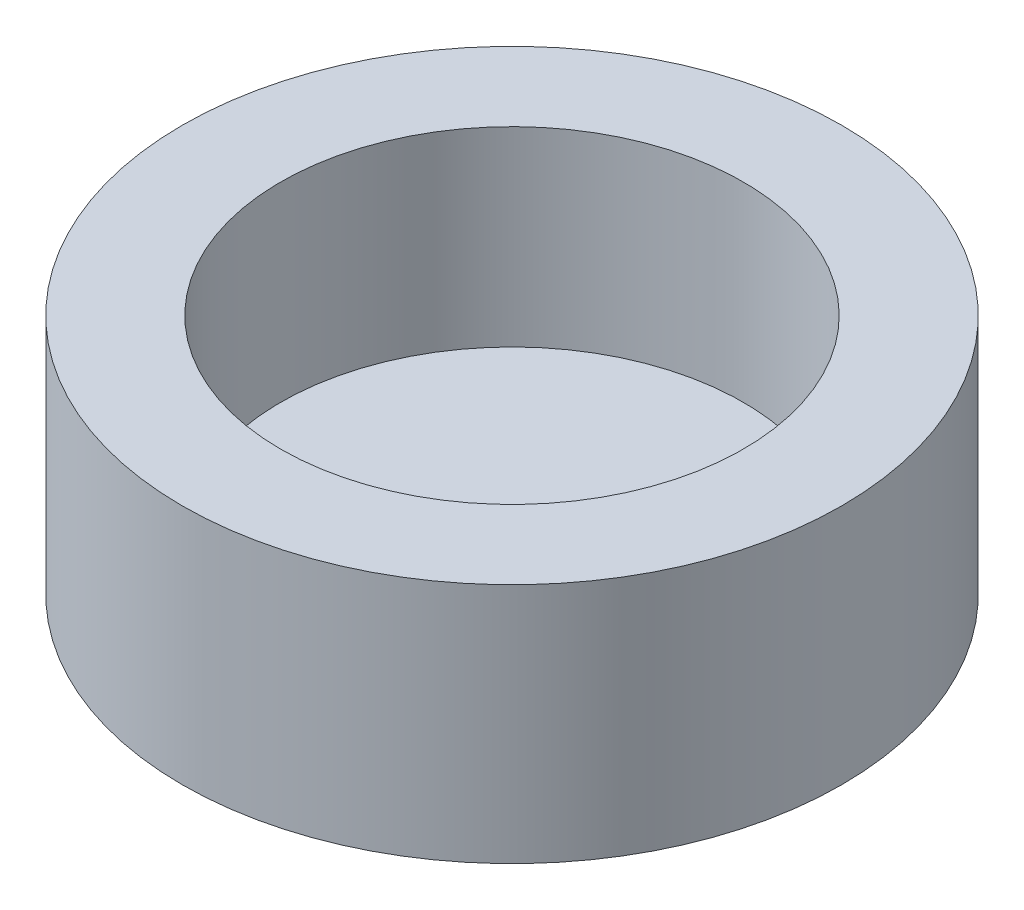
SolidWorks part; units mm, degrees
ref_plane "Front Plane" through (0, 0, 0) normal (0, 0, 1) x (1, 0, 0)
ref_plane "Top Plane" through (0, 0, 0) normal (0, 1, 0) x (1, 0, 0)
ref_plane "Right Plane" through (0, 0, 0) normal (1, 0, 0) x (0, 0, -1)
sketch "Sketch1" plane through (0, 0, 0) normal (0, 1, 0) x (1, 0, 0)
  circle A0 centre (0, 0) radius 34.671
  dimension "D1" = 69.342
extrude "Boss-Extrude2" add sketch "Sketch1" along normal blind 25.4
sketch "Sketch5" plane through (0, 25.4, 0) normal (0, 1, 0) x (1, 0, 0)
  circle A0 centre (0, 0) radius 24.3315
extrude "Cut-Extrude2" cut sketch "Sketch5" against normal blind 20.066
sketch "Sketch6" plane through (0, 5.334, 0) normal (0, 1, 0) x (1, 0, 0)
  circle A0 centre (0, 0) radius 24.3315 construction
  circle A1 centre (0, 0) radius 24.3315 construction
  spline S0 degree 2 poles (-11.7127, 21.3269) (7.2864, -5.5454) (-23.1265, 7.5625) knots 0 0 0 1 1 1
  spline S1 degree 2 poles (-24.2721, -1.6991) (6.5253, 5.0434) (-14.8678, -19.2606) knots 0 0 0 1 1 1
  spline S2 degree 2 poles (-9.2861, -22.4898) (0.6012, 9.6983) (7.911, -23.0095) knots 0 0 0 1 1 1
  spline S3 degree 2 poles (13.6303, -20.1554) (-6.2402, 7.8602) (23.4399, -6.5264) knots 0 0 0 1 1 1
  spline S4 degree 2 poles (-4.3356, 23.9421) (-1.6411, -7.5297) (11.7127, 21.3269) knots 0 0 0 1 1 1
  spline S5 degree 2 poles (16.9452, 17.4609) (-5.0365, 1.6251) (24.3284, -0.3903) knots 0 0 0 1 1 1
  point P21 (-5.0285, 4.4966)
  point P23 (-6.6724, -2.4659)
  point P24 (6.3823, -2.4659)
  point P25 (0.967, 7.5625)
